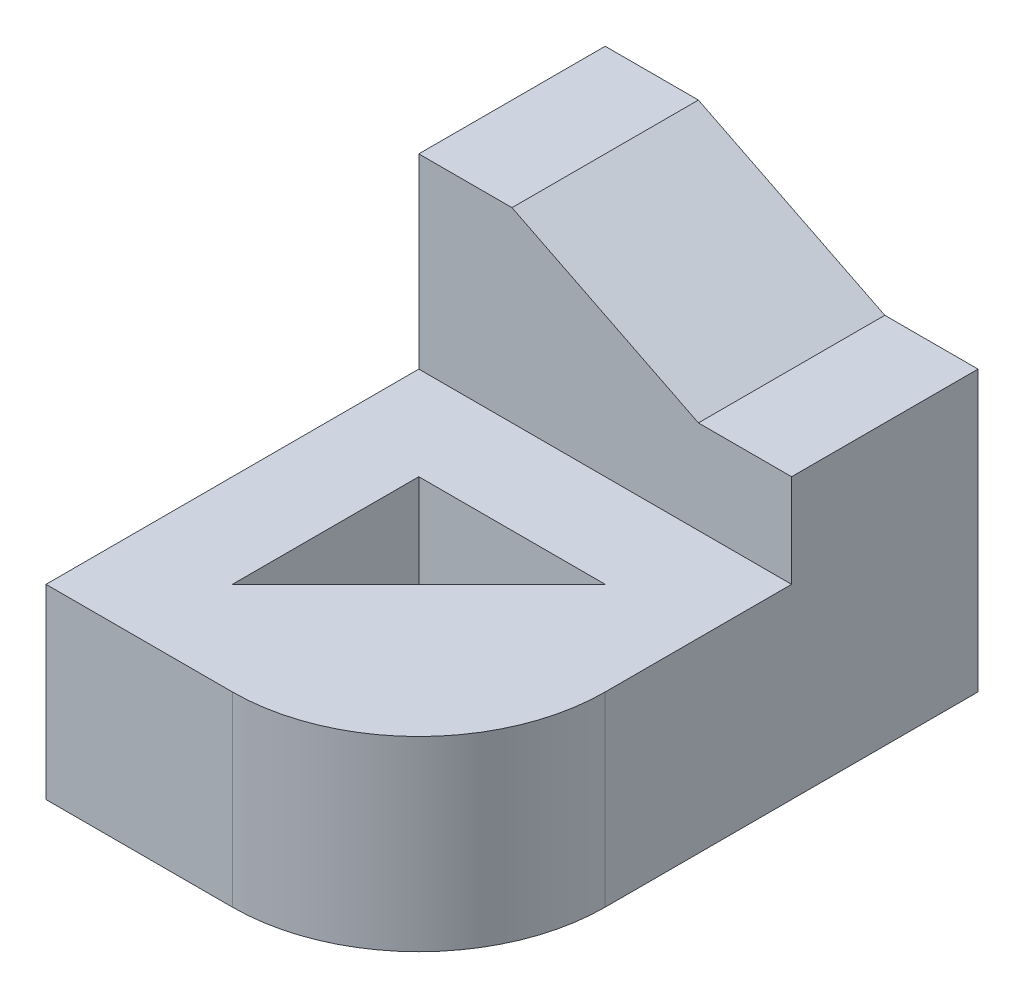
SolidWorks part; units mm, degrees
ref_plane "前基準面" through (0, 0, 0) normal (0, 0, 1) x (1, 0, 0)
ref_plane "上基準面" through (0, 0, 0) normal (0, 1, 0) x (1, 0, 0)
ref_plane "右基準面" through (0, 0, 0) normal (1, 0, 0) x (0, 0, -1)
sketch "草圖1" plane through (0, 0, 0) normal (0, 1, 0) x (1, 0, 0)
  line L1 (0, 0) -> (20, 0)
  line L2 (0, 0) -> (0, 30)
  line L3 (0, 30) -> (20, 30)
  line L4 (20, 0) -> (20, 30)
  dimension "D1" = 30
  dimension "D2" = 20
extrude "填料-伸長1" add sketch "草圖1" along normal blind 10
fillet "圓角1" radius 10 1 edges at (20, 5, 0)
sketch "草圖2" plane through (0, 10, 0) normal (0, 1, 0) x (1, 0, 0)
  line L0 (5, 15) -> (15, 15)
  line L1 (15, 15) -> (5, 5)
  line L2 (5, 5) -> (5, 15)
  line L3 (20, 10) -> (20, 30) construction
  line L4 (0, 30) -> (0, 0) construction
  line L5 (0, 0) -> (10, 0) construction
  dimension "D1" = 10
  dimension "D2" = 10
  dimension "D3" = 5
  dimension "D4" = 5
  dimension "D5" = 5
extrude "除料-伸長1" cut sketch "草圖2" against normal through all
sketch "草圖3" plane through (0, 0, -30) normal (0, 0, -1) x (-1, 0, 0)
  line L0 (0, 10) -> (0, 20)
  line L1 (0, 20) -> (-5, 20)
  line L2 (-5, 20) -> (-15, 15)
  line L3 (-15, 15) -> (-20, 15)
  line L4 (-20, 15) -> (-20, 10)
  line L5 (-20, 10) -> (0, 10)
  dimension "D1" = 10
  dimension "D2" = 5
  dimension "D3" = 5
  dimension "D4" = 10
extrude "填料-伸長2" add sketch "草圖3" against normal blind 10
